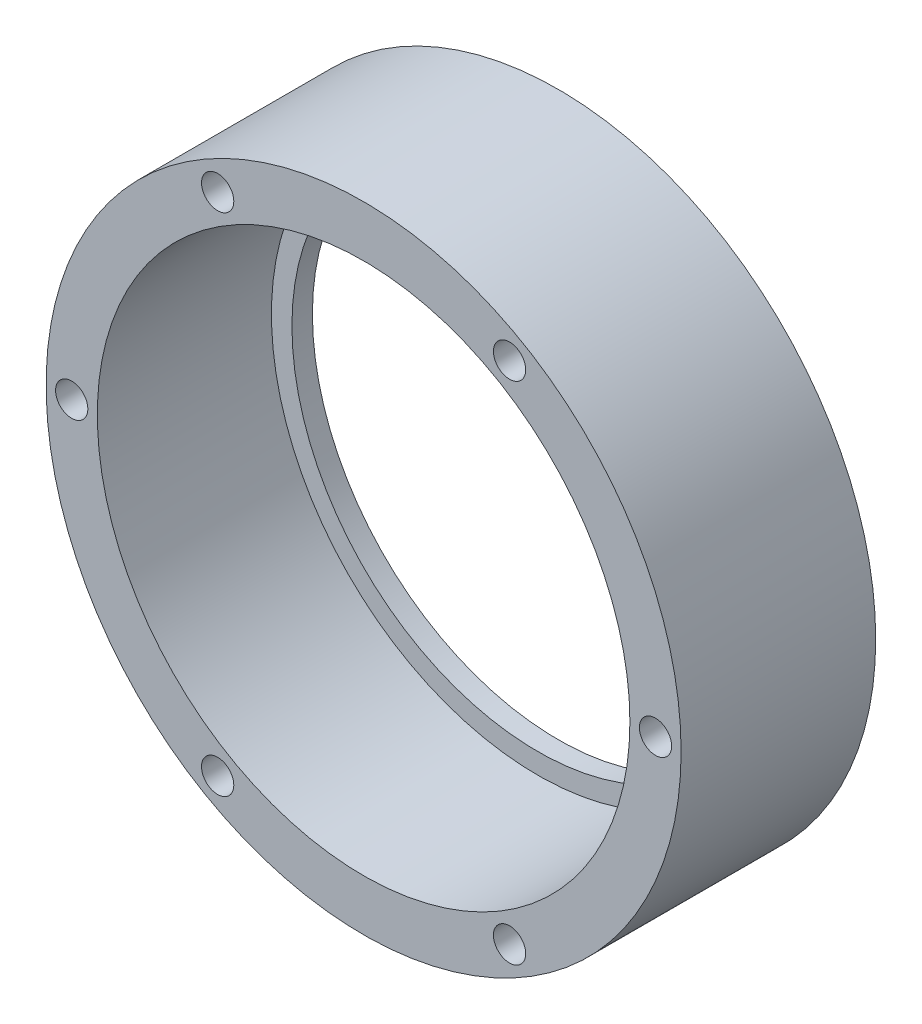
SolidWorks part; units mm, degrees
ref_plane "Спереди" through (0, 0, 0) normal (0, 0, 1) x (1, 0, 0)
ref_plane "Сверху" through (0, 0, 0) normal (0, 1, 0) x (1, 0, 0)
ref_plane "Справа" through (0, 0, 0) normal (1, 0, 0) x (0, 0, -1)
sketch "Эскиз1" plane through (0, 0, 0) normal (1, 0, 0) x (0, 0, -1)
  line L3 (0, 31) -> (19, 31)
  line L4 (19, 31) -> (19, 24)
  line L6 (19, 24) -> (17, 24)
  line L7 (17, 24) -> (17, 26)
  line L8 (17, 26) -> (0, 26)
  line L9 (0, 0) -> (56.4457, 0) construction
  line L10 (0, 26) -> (0, 31)
  dimension "D1" = 52
  dimension "D2" = 48
  dimension "D3" = 62
  dimension "D4" = 2
  dimension "D5" = 19
revolve "Повернуть1" add sketch "Эскиз1" angle 360 about L9
hole_wizard "Сверло под метчик  спиральное M31" positions "Эскиз2" profile "Эскиз3" hole size "M3x0.5" standard "DIN"
sketch "Эскиз2" plane through (0, 0, 0) normal (0, 0, 1) x (1, 0, 0)
  point P0 (28.5, 0)
  dimension "D1" = 28.5
sketch "Эскиз3" plane through (28.5, 0, 0) normal (1, 0, 0) x (0, -1, 0)
  line L0 (0, 0) -> (0, 8.9464)
  line L1 (0, 8.9464) -> (1.575, 8)
  line L2 (1.575, 8) -> (1.575, 0)
  line L5 (1.575, 0) -> (0, 0)
  line L10 (0, 8.9464) -> (-1.575, 8) construction
  line L11 (0, -6.35) -> (0, 107.95) construction
  dimension "Диаметр отверстия" = 3.15
  dimension "Глубина отверстия" = 8
  dimension "Угол заточки сверла" = 118
pattern_circular "Круговой массив1" count 6 over 360 about axis through (0, 0, 0) along (0, 0, 1) of "Сверло под метчик  спиральное M31"
